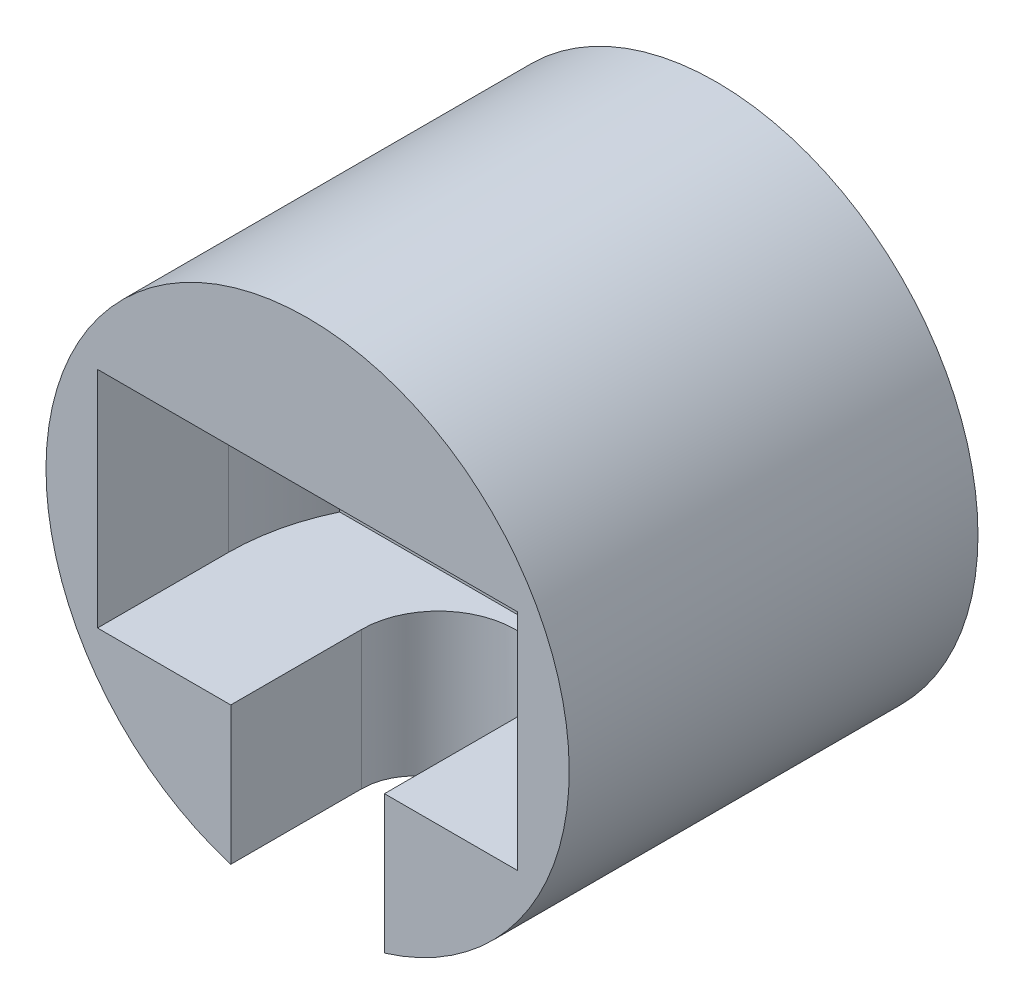
SolidWorks part; units mm, degrees
ref_plane "Front Plane" through (0, 0, 0) normal (0, 0, 1) x (1, 0, 0)
ref_plane "Top Plane" through (0, 0, 0) normal (0, 1, 0) x (1, 0, 0)
ref_plane "Right Plane" through (0, 0, 0) normal (1, 0, 0) x (0, 0, -1)
sketch "Sketch1" plane through (0, 0, 0) normal (0, 0, 1) x (1, 0, 0)
  circle A0 centre (0, 0) radius 3
  circle A1 centre (0, 0) radius 16
extrude "Boss-Extrude1" add sketch "Sketch1" along normal blind 25
sketch "Sketch2" plane through (0, 0, 0) normal (0, 1, 0) x (1, 0, 0)
  line L9 (-11.5897, -11.45) -> (11.5897, -11.45)
  line L10 (12.85, -25) -> (-12.85, -25)
  line L11 (12.85, -25) -> (12.85, -17)
  line L13 (-12.85, -25) -> (-12.85, -17)
  arc A5 (12.85, -17) -> (11.5897, -11.45) centre (0, -17) ccw
  arc A6 (-11.5897, -11.45) -> (-12.85, -17) centre (0, -17) ccw
extrude "Cut-Extrude1" cut sketch "Sketch2" against normal mid plane 13.7
sketch "Sketch3" plane through (0, 0, 0) normal (0, 1, 0) x (1, 0, 0)
  line L9 (-4.7, -17) -> (-4.7, -25)
  line L10 (-4.7, -25) -> (4.7, -25)
  line L11 (4.7, -17) -> (4.7, -25)
  arc A4 (4.7, -17) -> (-4.7, -17) centre (0, -17) ccw
extrude "Cut-Extrude2" cut sketch "Sketch3" against normal up to surface (15.2941 mm away)
